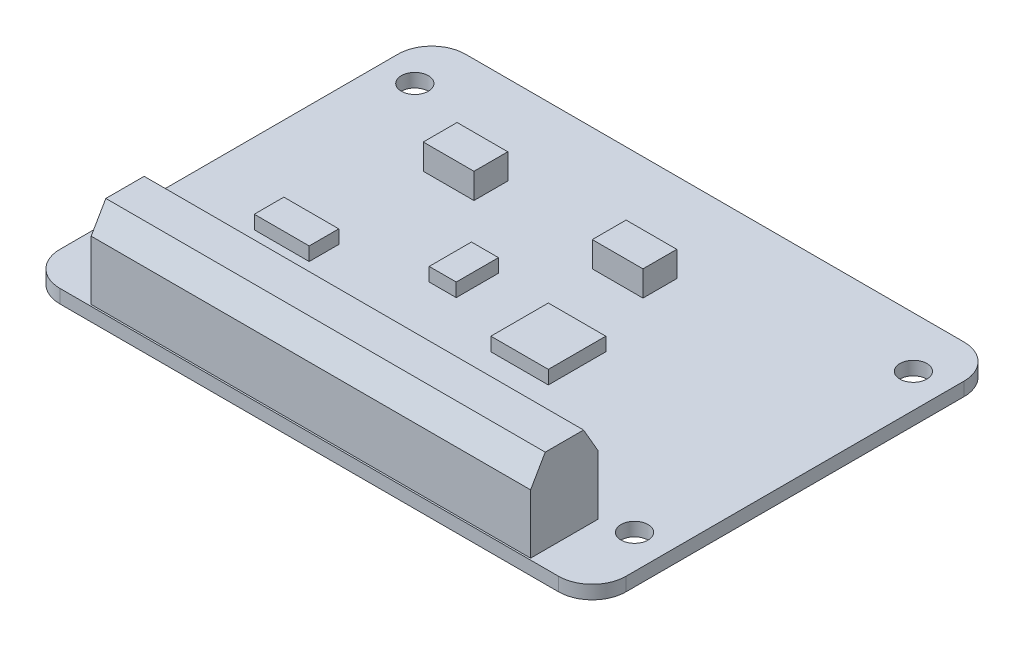
SolidWorks part; units mm, degrees
ref_plane "前视基准面" through (0, 0, 0) normal (0, 0, 1) x (1, 0, 0)
ref_plane "上视基准面" through (0, 0, 0) normal (0, 1, 0) x (1, 0, 0)
ref_plane "右视基准面" through (0, 0, 0) normal (1, 0, 0) x (0, 0, -1)
sketch "草图1" plane through (0, 0, 0) normal (0, 1, 0) x (1, 0, 0)
  line L1 (0, 0) -> (67, 0)
  line L2 (0, 0) -> (0, 48)
  line L3 (0, 48) -> (67, 48)
  line L4 (67, 0) -> (67, 48)
  dimension "D1" = 67
  dimension "D2" = 48
extrude "凸台-拉伸1" add sketch "草图1" along normal blind 1.6
fillet "圆角1" radius 4 4 edges at (0, 0.8, 0) (0, 0.8, -48) (67, 0.8, -48) (67, 0.8, 0)
hole_wizard "Ø3.2 (3.2) 直径孔1" positions "草图3" profile "草图2" hole size "Ø3.2" standard "GB" end condition through all
sketch "草图3" plane through (0, 1.6, 0) normal (0, 1, 0) x (1, 0, 0)
  point P0 (4, 9)
  point P2 (4, 42)
  point P4 (63, 42)
  point P6 (63, 9)
  dimension "D1" = 4
  dimension "D2" = 9
  dimension "D3" = 59
  dimension "D4" = 33
sketch "草图2" plane through (4, 1.6, -9) normal (1, 0, 0) x (0, 0, 1)
  line L0 (0, 0) -> (0, 1.6)
  line L1 (0, 1.6) -> (1.6, 1.6)
  line L2 (1.6, 1.6) -> (1.6, 0)
  line L5 (1.6, 0) -> (0, 0)
  line L11 (0, -6.35) -> (0, 107.95) construction
  dimension "通孔孔直径" = 3.2
  dimension "通孔孔深度" = 1.6
sketch "草图4" plane through (0, 1.6, 0) normal (0, 1, 0) x (1, 0, 0)
  line L0 (0, 44) -> (0, 4) construction
  line L1 (36, 19) -> (42.8, 19)
  line L2 (36, 19) -> (36, 25.8)
  line L3 (36, 25.8) -> (42.8, 25.8)
  line L4 (42.8, 19) -> (42.8, 25.8)
  line L5 (25.2, 27.5) -> (28.4, 27.5)
  line L6 (25.2, 27.5) -> (25.2, 22.5)
  line L7 (25.2, 22.5) -> (28.4, 22.5)
  line L8 (28.4, 27.5) -> (28.4, 22.5)
  line L9 (9.5, 21) -> (16, 21)
  line L10 (9.5, 21) -> (9.5, 17.5)
  line L11 (9.5, 17.5) -> (16, 17.5)
  line L12 (16, 21) -> (16, 17.5)
  line L13 (4, 0) -> (63, 0) construction
  dimension "D1" = 6.8
  dimension "D2" = 6.8
  dimension "D3" = 36
  dimension "D4" = 19
  dimension "D5" = 3.2
  dimension "D6" = 5
  dimension "D7" = 6.5
  dimension "D8" = 3.5
  dimension "D9" = 9.5
  dimension "D10" = 17.5
  dimension "D11" = 25.2
  dimension "D12" = 22.5
extrude "凸台-拉伸2" add sketch "草图4" along normal blind 1.6
sketch "草图5" plane through (0, 1.6, 0) normal (0, 1, 0) x (1, 0, 0)
  line L0 (0, 44) -> (0, 4) construction
  line L1 (7.5, 0.2) -> (59.5, 0.2)
  line L2 (7.5, 0.2) -> (7.5, 8.2)
  line L3 (7.5, 8.2) -> (59.5, 8.2)
  line L4 (59.5, 0.2) -> (59.5, 8.2)
  line L5 (4, 0) -> (63, 0) construction
  dimension "D1" = 52
  dimension "D2" = 8
  dimension "D3" = 7.5
  dimension "D4" = 0.2
extrude "凸台-拉伸4" add sketch "草图5" along normal blind 10
chamfer "倒角1" distance 3 angle 30 2 edges at (33.5, 11.6, -0.2) (33.5, 11.6, -8.2)
sketch "草图7" plane through (0, 1.6, 0) normal (0, 1, 0) x (1, 0, 0)
  line L0 (0, 44) -> (0, 4) construction
  line L1 (13.5, 37.5) -> (19.5, 37.5)
  line L2 (13.5, 37.5) -> (13.5, 33.5)
  line L3 (13.5, 33.5) -> (19.5, 33.5)
  line L4 (19.5, 37.5) -> (19.5, 33.5)
  line L5 (33.5, 37.5) -> (39.5, 37.5)
  line L6 (33.5, 37.5) -> (33.5, 33.5)
  line L7 (33.5, 33.5) -> (39.5, 33.5)
  line L8 (39.5, 37.5) -> (39.5, 33.5)
  line L9 (4, 0) -> (63, 0) construction
  dimension "D1" = 6
  dimension "D2" = 6
  dimension "D3" = 4
  dimension "D4" = 4
  dimension "D5" = 13.5
  dimension "D6" = 14
  dimension "D7" = 33.5
extrude "凸台-拉伸5" add sketch "草图7" along normal blind 3
